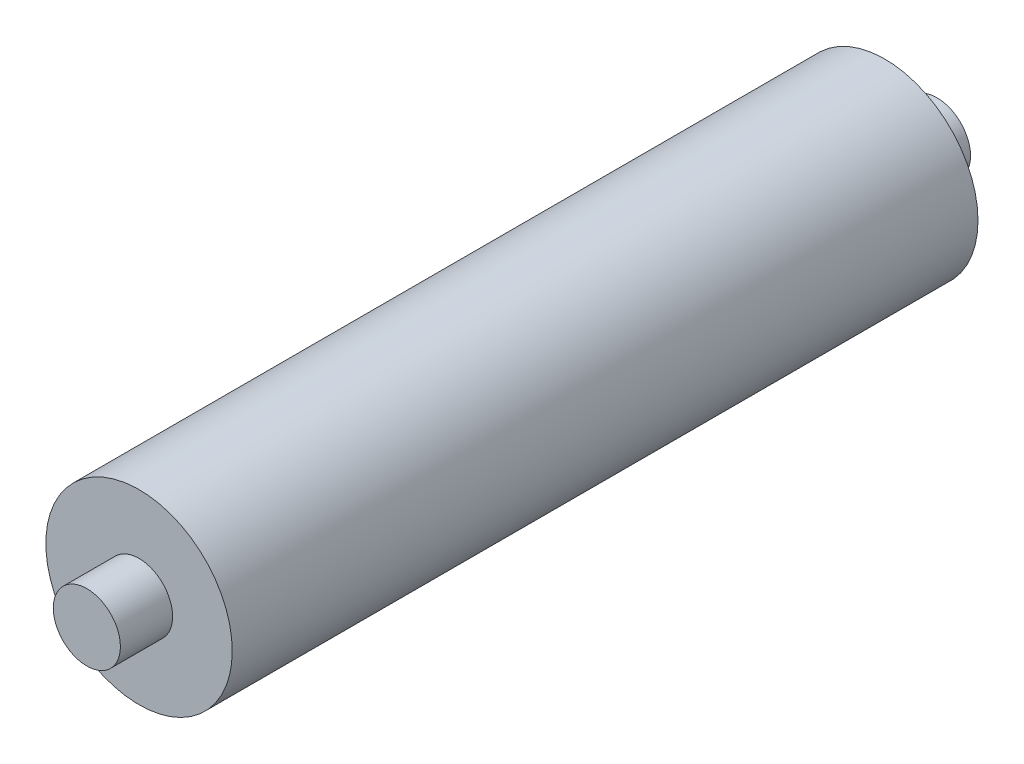
SolidWorks part; units mm, degrees
ref_plane "Front Plane" through (0, 0, 0) normal (0, 0, 1) x (1, 0, 0)
ref_plane "Top Plane" through (0, 0, 0) normal (0, 1, 0) x (1, 0, 0)
ref_plane "Right Plane" through (0, 0, 0) normal (1, 0, 0) x (0, 0, -1)
sketch "Sketch2" plane through (0, 0, 0) normal (0, 0, 1) x (1, 0, 0)
  circle A0 centre (0, 0) radius 4.5
  dimension "D1" = 9
extrude "Boss-Extrude1" add sketch "Sketch2" along normal blind 7
sketch "Sketch3" plane through (0, 0, 7) normal (0, 0, 1) x (1, 0, 0)
  circle A0 centre (0, 0) radius 12.5
  dimension "D1" = 25
extrude "Boss-Extrude2" add sketch "Sketch3" along normal blind 50
mirror "Mirror1" about plane through (0, 0, 57) normal (0, 0, 1) of bodies 102
